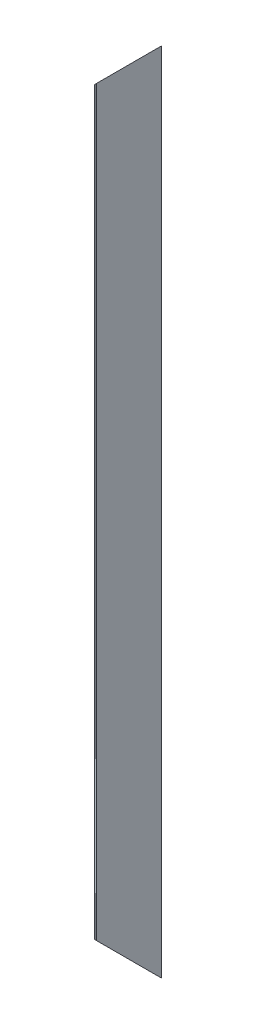
SolidWorks part; units mm, degrees
ref_plane "Front Plane" through (0, 0, 0) normal (0, 0, 1) x (1, 0, 0)
ref_plane "Top Plane" through (0, 0, 0) normal (0, 1, 0) x (1, 0, 0)
ref_plane "Right Plane" through (0, 0, 0) normal (1, 0, 0) x (0, 0, -1)
sketch "Sketch1" plane through (0, 0, 0) normal (0, 0, 1) x (1, 0, 0)
  line L0 (0, 0) -> (0, 500)
  dimension "D1" = 500
other "L angle (equal) 40X40X3(1)"
ref_plane "Plane1" through (0, 0, 0) normal (0, 1, 0) x (-1, 0, 0)
sketch "Sketch11" plane through (0, 0, 0) normal (0, 1, 0) x (-1, 0, 0)
  line L0 (0, 40) -> (0, 0)
  line L2 (3, 37) -> (3, 9)
  line L3 (9, 3) -> (37, 3)
  line L5 (40, 0) -> (0, 0)
  arc A0 (3, 37) -> (0, 40) centre (0, 37) ccw
  arc A1 (40, 0) -> (37, 3) centre (37, 0) ccw
  arc A2 (9, 3) -> (3, 9) centre (9, 9) cw
  point P8 (0, 20)
  point P9 (20, 0)
  point P10 (0, 0)
  dimension "Radius_2" = 3
  dimension "Radius_1" = 6
  dimension "V_leg" = 40
  dimension "H_leg" = 40
  dimension "thickness" = 3
sketch "Sketch17" plane through (0, 0, 0) normal (0, 0, -1) x (-1, 0, 0)
  line L1 (40, 460) -> (0, 500)
  line L4 (0, 0) -> (40, 0)
  line L5 (40, 0) -> (40, 500)
  line L6 (40, 500) -> (0, 500)
  line L7 (0, 500) -> (0, 0)
  line L8 (0, 0) -> (40, 0)
  line L9 (40, 460) -> (40, 500)
  line L10 (40, 500) -> (0, 500)
  line M6 (40, 0) -> (40, 500)
  line M7 (40, 500) -> (0, 500)
  dimension "D1" = 0
extrude "Cut-Extrude3" cut sketch "Sketch17" against normal through all contours L1 M6 M7
ref_plane "Plane4" through (0, 0, 0) normal (1, 0, 0) x (0, 0, -1)
sketch "Sketch18" plane through (0, 0, 0) normal (1, 0, 0) x (0, 0, -1)
  line L0 (0, 0) -> (-40, 0)
  line L1 (0, 0) -> (-40, 40)
  line L4 (-40, 0) -> (0, 0)
  line L5 (0, 0) -> (0, 500)
  line L6 (0, 500) -> (-40, 500)
  line L7 (-40, 500) -> (-40, 0)
  line L8 (-40, 0) -> (0, 0) construction
  line L10 (0, 500) -> (-40, 500)
  line L11 (-40, 40) -> (-40, 0)
  dimension "D1" = 0
extrude "Cut-Extrude4" cut sketch "Sketch18" against normal blind 40 contours L1 L11 L0
ref_plane "Plane5" through (0, 0, 0) normal (0, -0.7071, -0.7071) x (-1, 0, 0)
ref_plane "Plane6" through (0, 0, 0) normal (0, 0, -1) x (-1, 0, 0)
sketch "Sketch19" plane through (0, 0, 0) normal (0, 0, -1) x (-1, 0, 0)
  line L0 (0, 0) -> (40, 0) construction
  line L1 (0, 0) -> (40, 0) construction
  line L2 (0, 20) -> (40, 20) construction
  line L3 (0, 480) -> (40, 480) construction
  circle A0 centre (20, 480) radius 2
  circle A1 centre (20, 20) radius 2
extrude "Cut-Extrude5" cut sketch "Sketch19" against normal blind 3
